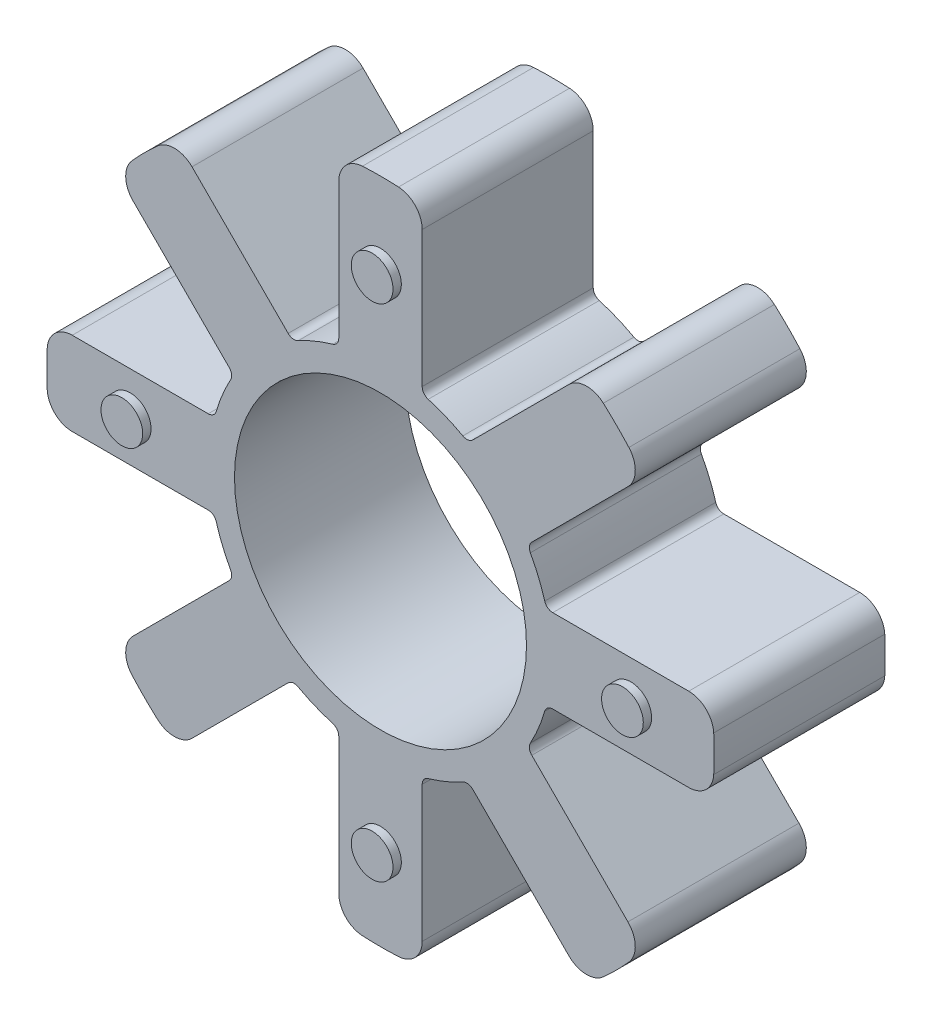
SolidWorks part; units mm, degrees
ref_plane "Front Plane" through (0, 0, 0) normal (0, 0, 1) x (1, 0, 0)
ref_plane "Top Plane" through (0, 0, 0) normal (0, 1, 0) x (1, 0, 0)
ref_plane "Right Plane" through (0, 0, 0) normal (1, 0, 0) x (0, 0, -1)
sketch "Sketch1" plane through (0, 0, 0) normal (0, 0, 1) x (1, 0, 0)
  circle A0 centre (0, 0) radius 17.5
  circle A1 centre (0, 0) radius 20.5
  dimension "D1" = 35
  dimension "D2" = 41
extrude "Boss-Extrude1" add sketch "Sketch1" along normal blind 20.5
sketch "Sketch4" plane through (0, 0, 20.5) normal (0, 0, 1) x (1, 0, 0)
  line L0 (-5, 19.8809) -> (-5, 39.6863)
  line L2 (5, 39.6863) -> (5, 19.8809)
  arc A0 (5, 39.6863) -> (-5, 39.6863) centre (0, 0) ccw
  circle A1 centre (0, 0) radius 20.5 construction
  circle A2 centre (0, 0) radius 20.5
  point P4 (0, 40)
  circle M4 centre (0, 0) radius 20.5
  dimension "D1" = 40
  dimension "D2" = 10
extrude "Boss-Extrude2" add sketch "Sketch4" against normal blind 20.5 contours L2 A0 L0 M4
fillet "Fillet1" radius 3 2 edges at (-5, 39.6863, 10.25) (5, 39.6863, 10.25)
fillet "Fillet2" radius 1 2 edges at (-5, 19.8809, 10.25) (5, 19.8809, 10.25)
pattern_circular "CirPattern1" count 8 over 360 about axis through (0, 0, 0) along (0, 0, 1) of "Fillet1", "Boss-Extrude2", "Fillet2"
sketch "Sketch5" plane through (0, 0, 20.5) normal (0, 0, 1) x (1, 0, 0)
  circle A0 centre (0, 30) radius 2.5
  dimension "D1" = 5
  dimension "D2" = 30
extrude "Boss-Extrude3" add sketch "Sketch5" along normal blind 1
sketch "Sketch6" plane through (0, 0, 0) normal (0, 0, -1) x (-1, 0, 0)
  line L0 (0, 0) -> (0, 32.4008) construction
  line L1 (-21.2132, 21.2132) -> (0, 0) construction
  circle A0 centre (-21.2132, 21.2132) radius 2.5
  dimension "D1" = 5
  dimension "D2" = 45
  dimension "D3" = 30
extrude "Boss-Extrude4" add sketch "Sketch6" along normal blind 1
pattern_circular "CirPattern2" count 4 over 360 about axis through (0, 0, 0) along (0, 0, 1) of "Boss-Extrude4", "Boss-Extrude3"
